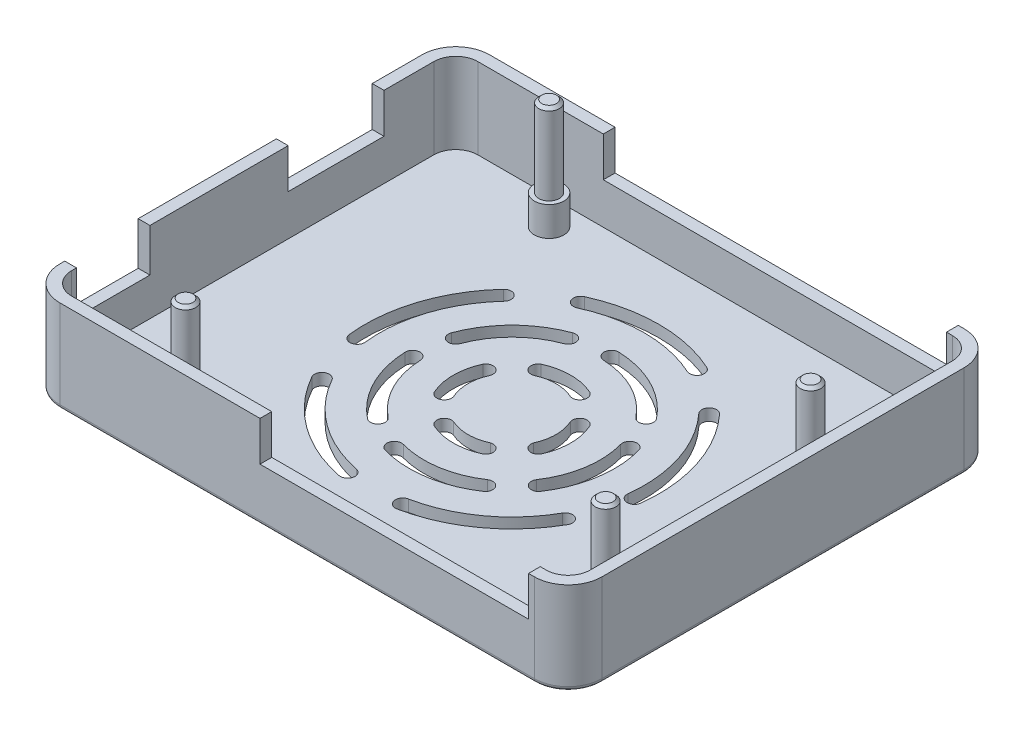
SolidWorks part; units mm, degrees
ref_plane "Front Plane" through (0, 0, 0) normal (0, 0, 1) x (1, 0, 0)
ref_plane "Top Plane" through (0, 0, 0) normal (0, 1, 0) x (1, 0, 0)
ref_plane "Right Plane" through (0, 0, 0) normal (1, 0, 0) x (0, 0, -1)
ref_plane "Plane1" through (0, 11, 0) normal (0, 1, 0) x (1, 0, 0)
sketch "Sketch1" plane through (0, 11, 0) normal (0, 1, 0) x (1, 0, 0)
  line L0 (-2.6, 55.9) -> (-2.6, -2.6)
  line L1 (-2.6, -2.6) -> (71.2, -2.6)
  line L2 (71.2, -2.6) -> (71.2, 55.9)
  line L3 (71.2, 55.9) -> (-2.6, 55.9)
extrude "Boss-Extrude1" add sketch "Sketch1" against normal blind 12.6
sketch "Sketch2" plane through (0, 11, 0) normal (0, 1, 0) x (-1, 0, 0)
  line L0 (1, 1) -> (-69.6, 1)
  line L1 (-69.6, 1) -> (-69.6, -54.3)
  line L2 (-69.6, -54.3) -> (1, -54.3)
  line L3 (1, -54.3) -> (1, 1)
extrude "Cut-Extrude1" cut sketch "Sketch2" against normal blind 11
sketch "Sketch3" plane through (-2.6, 0, 0) normal (-1, 0, 0) x (0, 0, 1)
  line L0 (-44.52, 11) -> (-44.52, 5.58)
  line L1 (-44.52, 5.58) -> (-31.48, 5.58)
  line L2 (-31.48, 5.58) -> (-31.48, 11)
  line L3 (-31.48, 11) -> (-44.52, 11)
extrude "Cut-Extrude2" cut sketch "Sketch3" against normal up to next
sketch "Sketch4" plane through (-2.6, 0, 0) normal (-1, 0, 0) x (0, 0, 1)
  line L0 (-12.655, 11) -> (-12.655, 5.15)
  line L1 (-12.655, 5.15) -> (-2.655, 5.15)
  line L2 (-2.655, 5.15) -> (-2.655, 11)
  line L3 (-2.655, 11) -> (-12.655, 11)
extrude "Cut-Extrude3" cut sketch "Sketch4" against normal up to next
ref_plane "Plane2" through (0, 0, -50.7) normal (0, 0, -1) x (-1, 0, 0)
sketch "Sketch5" plane through (0, 0, -50.7) normal (0, 0, -1) x (-1, 0, 0)
  line L0 (-17.3, 0) -> (-15.3, 0)
  line L1 (-15.3, 0) -> (-15.3, 15)
  line L2 (-15.3, 15) -> (-16.7, 15)
  line L3 (-16.7, 15) -> (-16.7, 4)
  line L4 (-16.7, 4) -> (-17.3, 4)
  line L5 (-17.3, 4) -> (-17.3, 0)
  line L6 (-15.3, 0) -> (-15.3, 15) construction
revolve "Revolve1" add sketch "Sketch5" angle 360 about L6
ref_plane "Plane3" through (0, 0, -35.5) normal (0, 0, -1) x (-1, 0, 0)
sketch "Sketch6" plane through (0, 0, -35.5) normal (0, 0, -1) x (-1, 0, 0)
  line L0 (-68.1, 0) -> (-66.1, 0)
  line L1 (-66.1, 0) -> (-66.1, 15)
  line L2 (-66.1, 15) -> (-67.5, 15)
  line L3 (-67.5, 15) -> (-67.5, 4)
  line L4 (-67.5, 4) -> (-68.1, 4)
  line L5 (-68.1, 4) -> (-68.1, 0)
  line L6 (-66.1, 0) -> (-66.1, 15) construction
revolve "Revolve2" add sketch "Sketch6" angle 360 about L6
ref_plane "Plane4" through (0, 0, -2.5) normal (0, 0, -1) x (-1, 0, 0)
sketch "Sketch7" plane through (0, 0, -2.5) normal (0, 0, -1) x (-1, 0, 0)
  line L0 (-16, 0) -> (-14, 0)
  line L1 (-14, 0) -> (-14, 15)
  line L2 (-14, 15) -> (-15.4, 15)
  line L3 (-15.4, 15) -> (-15.4, 4)
  line L4 (-15.4, 4) -> (-16, 4)
  line L5 (-16, 4) -> (-16, 0)
  line L6 (-14, 0) -> (-14, 15) construction
revolve "Revolve3" add sketch "Sketch7" angle 360 about L6
ref_plane "Plane5" through (0, 0, -7.6) normal (0, 0, -1) x (-1, 0, 0)
sketch "Sketch8" plane through (0, 0, -7.6) normal (0, 0, -1) x (-1, 0, 0)
  line L0 (-68.1, 0) -> (-66.1, 0)
  line L1 (-66.1, 0) -> (-66.1, 15)
  line L2 (-66.1, 15) -> (-67.5, 15)
  line L3 (-67.5, 15) -> (-67.5, 4)
  line L4 (-67.5, 4) -> (-68.1, 4)
  line L5 (-68.1, 4) -> (-68.1, 0)
  line L6 (-66.1, 0) -> (-66.1, 15) construction
revolve "Revolve4" add sketch "Sketch8" angle 360 about L6
fillet "Fillet1" radius 4.6 4 edges at (-2.6, 4.7, 2.6) (-2.6, 4.7, -55.9) (71.2, 4.7, 2.6) (71.2, 4.7, -55.9)
chamfer "Chamfer1" distance 0.4 angle 45 4 edges at (14, 15, -1.1) (66.1, 15, -34.1) (66.1, 15, -6.2) (15.3, 15, -49.3)
fillet "Fillet2" radius 0.6 8 edges at (69.8527, -1.6, -54.5527) (71.2, -1.6, -26.65) (34.3, -1.6, -55.9) (69.8527, -1.6, 1.2527) (-1.2527, -1.6, -54.5527) (34.3, -1.6, 2.6) (-2.6, -1.6, -26.65) (-1.2527, -1.6, 1.2527)
fillet "Fillet3" radius 3 4 edges at (-1, 5.5, 1) (69.6, 5.5, 1) (69.6, 5.5, -54.3) (-1, 5.5, -54.3)
sketch "Sketch9" plane through (0, 0, 0) normal (0, 1, 0) x (1, 0, 0)
  line L0 (-0.1213, 53.4213) -> (68.7213, -0.1213) construction
  line L1 (68.7213, 53.4213) -> (0, 0) construction
  line L2 (34.3, 46.65) -> (34.3, 6.65) construction
  line L3 (14.3, 26.65) -> (54.3, 26.65) construction
  line L4 (26.8, 43.0131) -> (25.9667, 44.8312) construction
  line L5 (31.8, 32.1044) -> (31.1633, 34.0094) construction
  line L6 (23.0508, 30.8281) -> (21.176, 31.5244) construction
  line L7 (34.3, 26.65) -> (20.1579, 40.7921) construction
  line L8 (-1, 51.3) -> (-1, 2) construction
  arc A0 (2, 54.3) -> (-1, 51.3) centre (2, 51.3) ccw construction
  arc A1 (66.6, -1) -> (69.6, 2) centre (66.6, 2) ccw construction
  arc A2 (69.6, 51.3) -> (66.6, 54.3) centre (66.6, 51.3) ccw construction
  circle A3 centre (34.3, 26.65) radius 20
  circle A4 centre (34.3, 26.65) radius 18
  arc A5 (26.8, 43.0131) -> (25.9667, 44.8312) centre (26.3833, 43.9221) cw
  arc A6 (41.8, 43.0131) -> (42.6333, 44.8312) centre (42.2167, 43.9221) ccw
  arc A7 (47.5446, 38.8394) -> (49.0162, 40.1938) centre (48.2804, 39.5166) cw
  arc A8 (52.1798, 24.5735) -> (54.1665, 24.3428) centre (53.1732, 24.4582) ccw
  arc A9 (49.9856, 17.8204) -> (51.7284, 16.8393) centre (50.857, 17.3299) cw
  arc A10 (37.8503, 9.0036) -> (38.2448, 7.0429) centre (38.0476, 8.0233) ccw
  arc A11 (30.7497, 9.0036) -> (30.3552, 7.0429) centre (30.5524, 8.0233) cw
  arc A12 (18.6144, 17.8204) -> (16.8716, 16.8393) centre (17.743, 17.3299) ccw
  circle A13 centre (34.3, 26.65) radius 14
  circle A14 centre (34.3, 26.65) radius 12
  arc A15 (23.0508, 30.8281) -> (21.176, 31.5244) centre (22.1134, 31.1763) cw
  arc A16 (30.1219, 37.8992) -> (29.4256, 39.774) centre (29.7737, 38.8366) ccw
  arc A17 (43.7075, 34.0998) -> (45.2754, 35.3414) centre (44.4914, 34.7206) ccw
  arc A18 (34.7974, 38.6397) -> (34.8803, 40.638) centre (34.8389, 39.6388) cw
  arc A19 (44.2922, 20.0051) -> (45.9576, 18.8976) centre (45.1249, 19.4513) ccw
  arc A20 (45.8566, 29.8819) -> (47.7827, 30.4206) centre (46.8196, 30.1513) cw
  arc A21 (31.0681, 15.0934) -> (30.5294, 13.1673) centre (30.7987, 14.1304) ccw
  arc A22 (40.9449, 16.6578) -> (42.0524, 14.9924) centre (41.4987, 15.8251) cw
  circle A23 centre (34.3, 26.65) radius 8
  circle A24 centre (34.3, 26.65) radius 6
  arc A25 (31.8, 32.1044) -> (31.1633, 34.0094) centre (31.4817, 33.0569) cw
  arc A26 (36.8, 32.1044) -> (37.4367, 34.0094) centre (37.1183, 33.0569) ccw
  arc A27 (39.7544, 29.15) -> (41.6594, 29.7867) centre (40.7069, 29.4683) cw
  arc A28 (39.7544, 24.15) -> (41.6594, 23.5133) centre (40.7069, 23.8317) ccw
  arc A29 (36.8, 21.1956) -> (37.4367, 19.2906) centre (37.1183, 20.2431) cw
  arc A30 (31.8, 21.1956) -> (31.1633, 19.2906) centre (31.4817, 20.2431) ccw
  arc A31 (28.8456, 24.15) -> (26.9406, 23.5133) centre (27.8931, 23.8317) cw
  arc A32 (28.8456, 29.15) -> (26.9406, 29.7867) centre (27.8931, 29.4683) ccw
  arc A33 (22.3103, 26.1526) -> (20.312, 26.0697) centre (21.3112, 26.1111) ccw
  arc A34 (26.8502, 17.2425) -> (25.6086, 15.6746) centre (26.2294, 16.4586) cw
  arc A35 (16.4202, 24.5735) -> (14.4335, 24.3428) centre (15.4268, 24.4582) cw
  arc A36 (21.0554, 38.8394) -> (19.5838, 40.1938) centre (20.3196, 39.5166) ccw
  dimension "D1" = 40
  dimension "D2" = 1.0043
  dimension "D3" = 7.5
  dimension "D7" = 5
  dimension "D8" = 45
  dimension "D12" = 2.5
  dimension "D6" = 2
  dimension "D10" = 4
  dimension "D11" = 2
  dimension "D4" = 5
  dimension "D9" = 5
  dimension "D13" = 4
extrude "Cut-Extrude4" cut sketch "Sketch9" against normal blind 10 contours A24 A26 A23 A25 | A24 A32 A23 A31 | A24 A30 A23 A29 | A24 A28 A23 A27 | A20 A14 A19 A13 | A22 A14 A21 A13 | A14 A16 A13 A15 | A18 A14 A17 A13 | A4 A6 A3 A5 | A4 A12 A3 A11 | A4 A10 A3 A9 | A4 A8 A3 A7 | A4 A36 A3 A35 | A34 A14 A33 A13
sketch "Esboço1" plane through (0, 0, 2.6) normal (0, 0, 1) x (1, 0, 0)
  line L0 (64.1, 4) -> (77.5487, 4) construction
  line L1 (2, 11) -> (77.5487, 11) construction
  line L3 (69.6, 0) -> (69.6, 21.2656) construction
  line L6 (65.8, 0) -> (65.8, 21.2656) construction
  line L7 (2, 0) -> (66.6, 0) construction
  line L8 (64.7, 5.6) -> (77.5487, 5.6) construction
  line L10 (64.7, 14.6) -> (64.7, 4) construction
  line L11 (65.8, 11) -> (29.24, 11)
  line L12 (65.8, 11) -> (65.8, 5.6)
  line L13 (65.8, 5.6) -> (29.24, 5.6)
  line L14 (29.24, 5.6) -> (29.24, 11)
  dimension "D1" = 7
  dimension "D3" = 1.6
  dimension "D4" = 5.4
  dimension "D5" = 36.56
  dimension "D2" = 3.8
extrude "Corte-extrusão1" cut sketch "Esboço1" against normal blind 6
sketch "Esboço2" plane through (0, 0, -55.9) normal (0, 0, -1) x (-1, 0, 0)
  line L0 (-64.1, 4) -> (-76.0031, 4) construction
  line L1 (-64.1, 4) -> (-68.1, 4) construction
  line L2 (-2, 11) -> (-76.0031, 11) construction
  line L3 (-69.6, 0) -> (-69.6, 20.7486) construction
  line L4 (-65.8, 4) -> (-65.8, 20.7486) construction
  line L5 (-64.1, 5.6) -> (-76.0031, 5.6) construction
  line L6 (-65.8, 11) -> (-65.8, 5.6)
  line L7 (-65.8, 11) -> (-19.08, 11)
  line L8 (-19.08, 11) -> (-19.08, 5.6)
  line L9 (-19.08, 5.6) -> (-65.8, 5.6)
  dimension "D1" = 7
  dimension "D2" = 3.8
  dimension "D3" = 1.6
  dimension "D4" = 46.72
extrude "Corte-extrusão2" cut sketch "Esboço2" against normal blind 6
